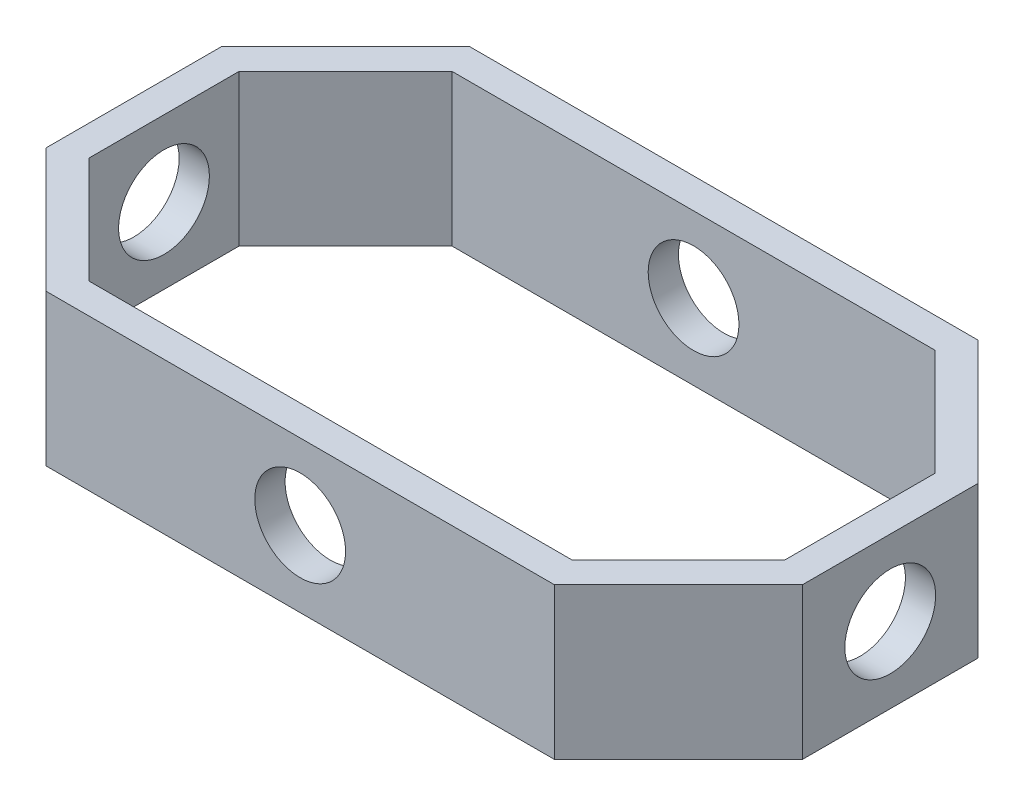
SolidWorks part; units mm, degrees
material "ABS"
ref_plane "Front Plane" through (0, 0, 0) normal (0, 0, 1) x (1, 0, 0)
ref_plane "Top Plane" through (0, 0, 0) normal (0, 1, 0) x (1, 0, 0)
ref_plane "Right Plane" through (0, 0, 0) normal (1, 0, 0) x (0, 0, -1)
sketch "Sketch3" plane through (0, 0, 0) normal (0, 1, 0) x (1, 0, 0)
  line L0 (-11, 0) -> (11, 0) construction
  line L17 (-16.799, -14) -> (16.799, -14)
  line L18 (3, 5.799) -> (-5.201, 14) construction
  line L19 (-5.201, 14) -> (-16.799, 14) construction
  line L20 (-16.799, 14) -> (-25, 5.799) construction
  line L21 (-25, 5.799) -> (-25, -5.799) construction
  line L22 (-25, -5.799) -> (-16.799, -14) construction
  line L23 (-16.799, -14) -> (-5.201, -14) construction
  line L24 (-5.201, -14) -> (3, -5.799) construction
  line L25 (3, -5.799) -> (3, 5.799) construction
  line L26 (-3, 5.799) -> (-3, -5.799) construction
  line L27 (-3, -5.799) -> (5.201, -14) construction
  line L28 (5.201, -14) -> (16.799, -14) construction
  line L29 (16.799, -14) -> (25, -5.799) construction
  line L30 (25, -5.799) -> (25, 5.799) construction
  line L31 (25, 5.799) -> (16.799, 14) construction
  line L32 (16.799, 14) -> (5.201, 14) construction
  line L33 (5.201, 14) -> (-3, 5.799) construction
  line L34 (16.799, -14) -> (25, -5.799)
  line L35 (25, -5.799) -> (25, 5.799)
  line L36 (25, 5.799) -> (16.799, 14)
  line L37 (16.799, 14) -> (-16.799, 14)
  line L38 (-16.799, 14) -> (-25, 5.799)
  line L39 (-25, 5.799) -> (-25, -5.799)
  line L40 (-25, -5.799) -> (-16.799, -14)
  line L41 (-23, -4.9706) -> (-15.9706, -12)
  line L42 (-15.9706, -12) -> (15.9706, -12)
  line L43 (15.9706, -12) -> (23, -4.9706)
  line L44 (23, -4.9706) -> (23, 4.9706)
  line L45 (23, 4.9706) -> (15.9706, 12)
  line L46 (15.9706, 12) -> (-15.9706, 12)
  line L47 (-15.9706, 12) -> (-23, 4.9706)
  line L48 (-23, 4.9706) -> (-23, -4.9706)
  circle A0 centre (-11, 0) radius 14 construction
  circle A1 centre (11, 0) radius 14 construction
  point P3 (0, 0)
  dimension "D1" = 50
  dimension "D2" = 28
  dimension "D3" = 24
ref_axis "Axis1" through (0, 0, 0) along (0, 1, 0)
extrude "Boss-Extrude2" add sketch "Sketch3" along normal blind 10
sketch "Sketch4" plane through (0, 0, 14) normal (0, 0, 1) x (1, 0, 0)
  line L0 (-16.799, 10) -> (-16.799, 0) construction
  circle A0 centre (0, 5) radius 3
  point P6 (-16.799, 5)
  dimension "D1" = 6
extrude "Cut-Extrude2" cut sketch "Sketch4" against normal up to next
pattern_circular "CirPattern2" count 4 over 360 about axis through (0, 0, 0) along (0, 1, 0) of "Cut-Extrude2"
